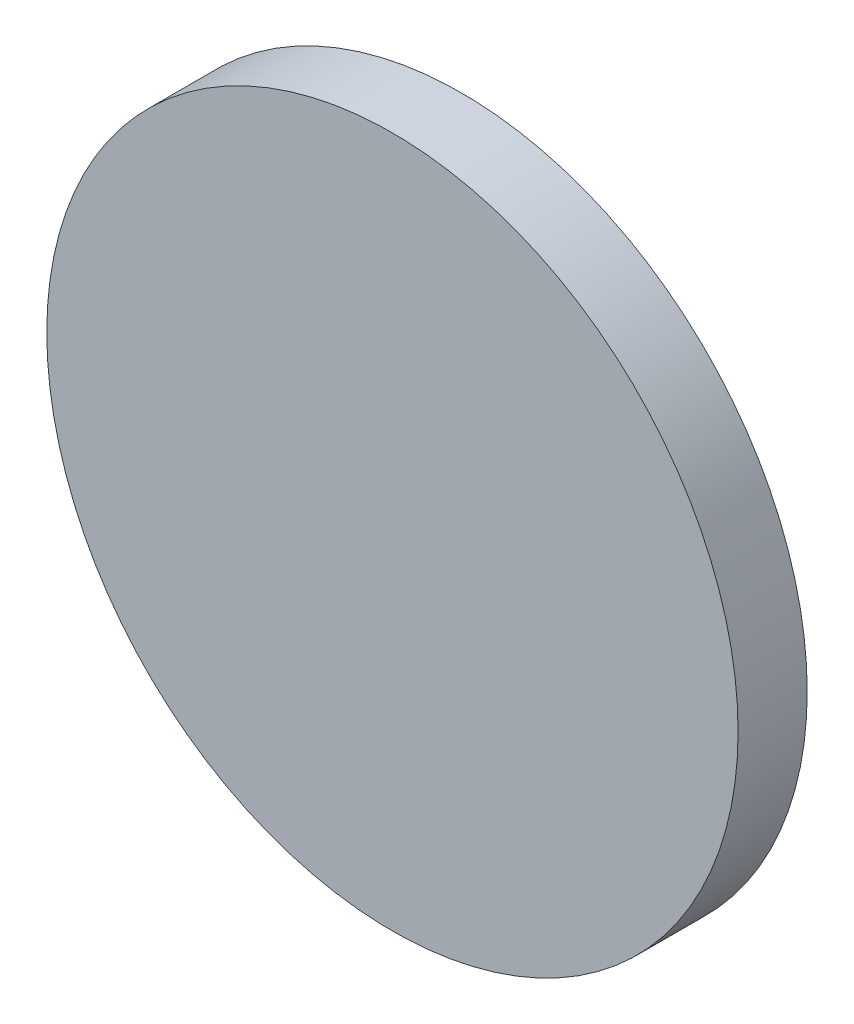
SolidWorks part; units mm, degrees
ref_plane "Front Plane" through (0, 0, 0) normal (0, 0, 1) x (1, 0, 0)
ref_plane "Top Plane" through (0, 0, 0) normal (0, 1, 0) x (1, 0, 0)
ref_plane "Right Plane" through (0, 0, 0) normal (1, 0, 0) x (0, 0, -1)
sketch "Sketch1" plane through (0, 0, 0) normal (0, 0, 1) x (1, 0, 0)
  circle A0 centre (0, 0) radius 25.4
extrude "Boss-Extrude1" add sketch "Sketch1" along normal blind 5.08
sketch "Sketch2" plane through (0, 0, 5.08) normal (0, 0, 1) x (1, 0, 0)
  circle A0 centre (0, 0) radius 2.54
